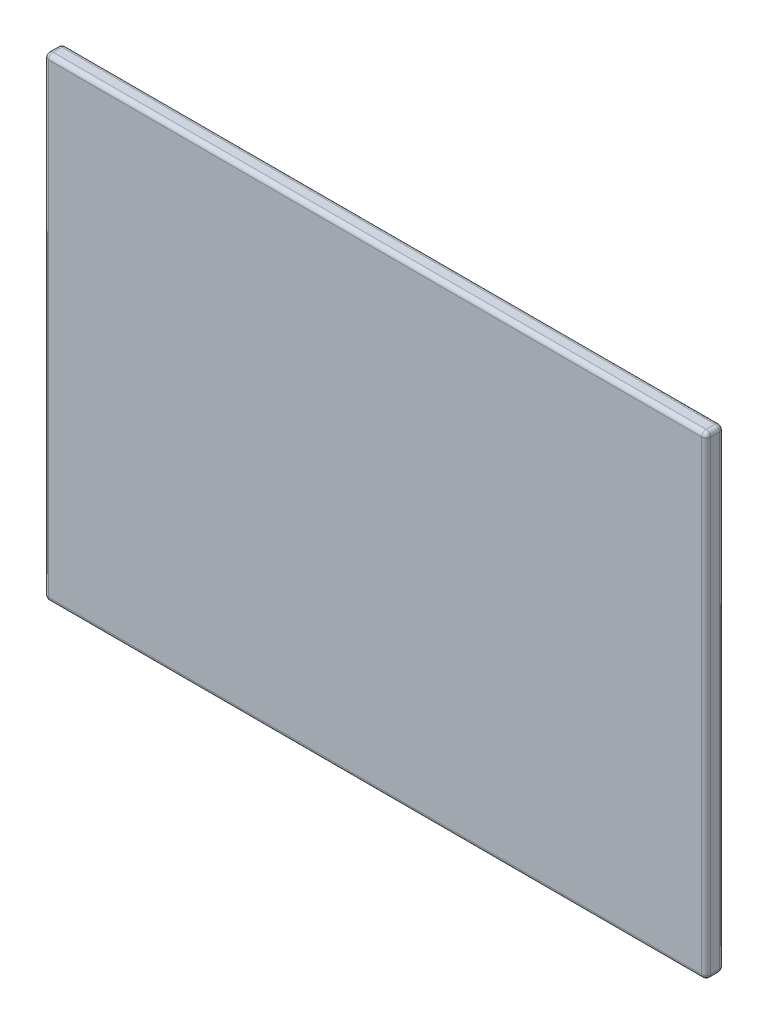
SolidWorks part; units mm, degrees
ref_plane "Front Plane" through (0, 0, 0) normal (0, 0, 1) x (1, 0, 0)
ref_plane "Top Plane" through (0, 0, 0) normal (0, 1, 0) x (1, 0, 0)
ref_plane "Right Plane" through (0, 0, 0) normal (1, 0, 0) x (0, 0, -1)
sketch "Sketch1" plane through (0, 0, 0) normal (0, 0, 1) x (1, 0, 0)
  line L1 (-37.35, -26.75) -> (37.35, -26.75)
  line L2 (-37.35, -26.75) -> (-37.35, 26.75)
  line L3 (-37.35, 26.75) -> (37.35, 26.75)
  line L4 (37.35, -26.75) -> (37.35, 26.75)
  line L5 (-37.35, -26.75) -> (37.35, 26.75) construction
  line L6 (-37.35, 26.75) -> (37.35, -26.75) construction
  point P0 (0, 0)
  dimension "D1" = 74.7
  dimension "D2" = 53.5
extrude "Boss-Extrude1" add sketch "Sketch1" along normal blind 2
fillet "Fillet1" radius 0.5 12 edges at (0, -26.75, 2) (0, -26.75, 0) (-37.35, 0, 2) (-37.35, -26.75, 1) (-37.35, 0, 0) (0, 26.75, 2) (-37.35, 26.75, 1) (0, 26.75, 0) (37.35, -26.75, 1) (37.35, 0, 2) (37.35, 26.75, 1) (37.35, 0, 0)
